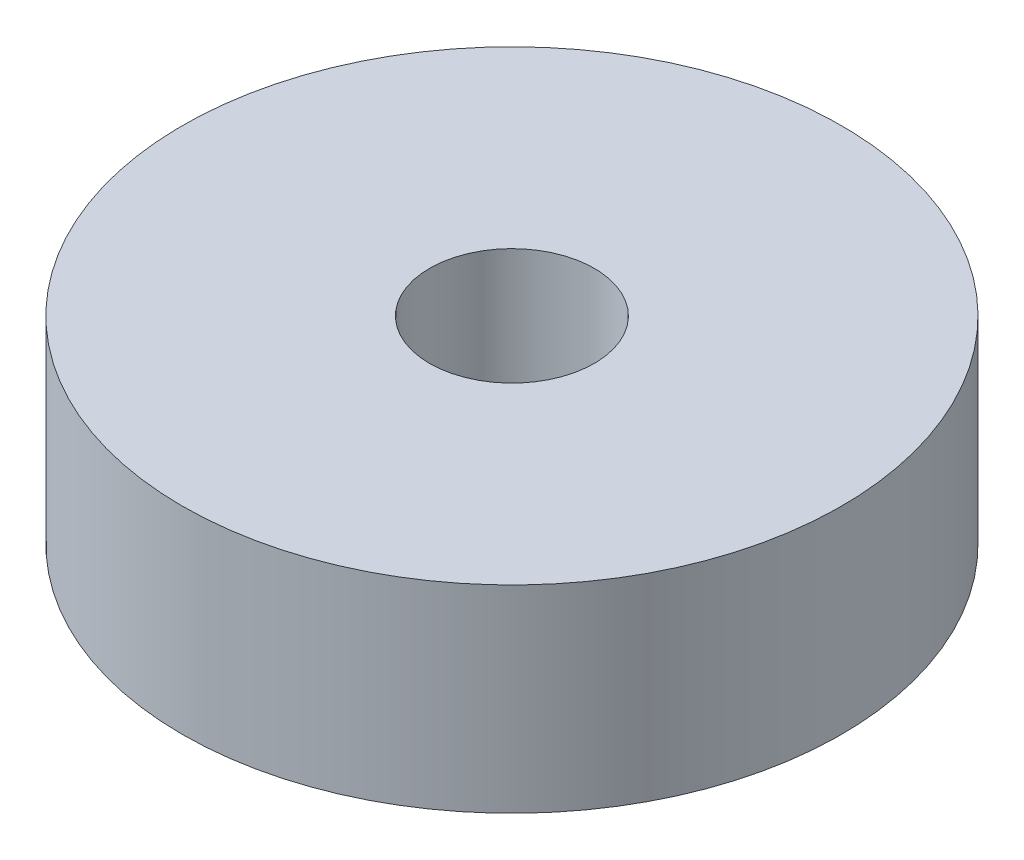
SolidWorks part; units mm, degrees
ref_plane "Front Plane" through (0, 0, 0) normal (0, 0, 1) x (1, 0, 0)
ref_plane "Top Plane" through (0, 0, 0) normal (0, 1, 0) x (1, 0, 0)
ref_plane "Right Plane" through (0, 0, 0) normal (1, 0, 0) x (0, 0, -1)
sketch "Sketch1" plane through (0, 0, 0) normal (0, 1, 0) x (1, 0, 0)
  circle A0 centre (0, 0) radius 100
  dimension "D1" = 200
extrude "Boss-Extrude1" add sketch "Sketch1" along normal blind 60
sketch "Sketch2" plane through (0, 60, 0) normal (0, 1, 0) x (1, 0, 0)
  circle A0 centre (0, 0) radius 25
  dimension "D1" = 50
extrude "Cut-Extrude1" cut sketch "Sketch2" against normal blind 50
